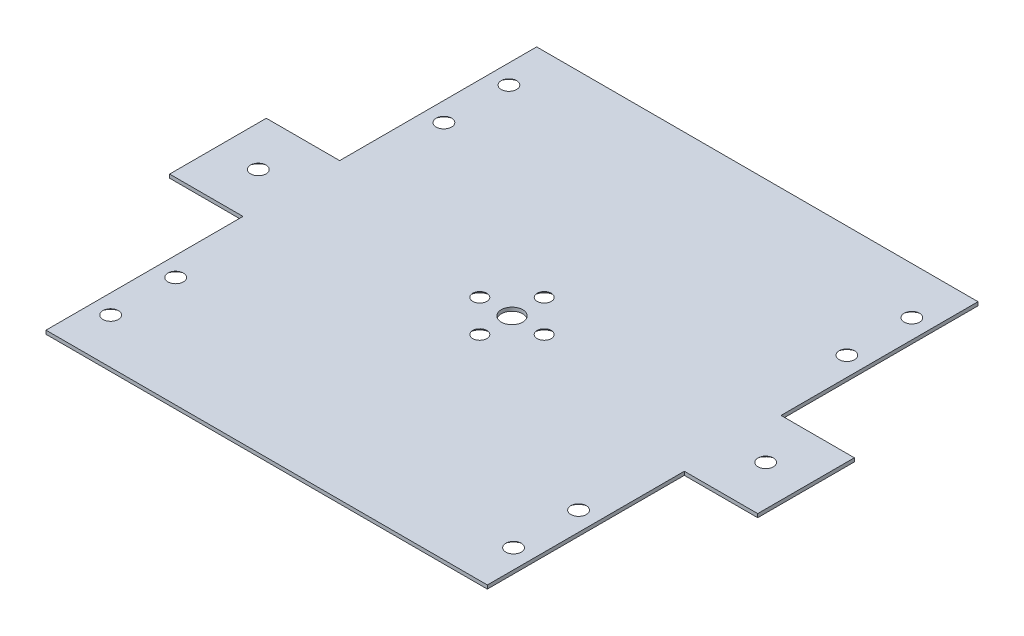
SolidWorks part; units mm, degrees
material "Plain Carbon Steel"
ref_plane "Front Plane" through (0, 0, 0) normal (0, 0, 1) x (1, 0, 0)
ref_plane "Top Plane" through (0, 0, 0) normal (0, 1, 0) x (1, 0, 0)
ref_plane "Right Plane" through (0, 0, 0) normal (1, 0, 0) x (0, 0, -1)
sketch "Sketch1" plane through (0, 0, 0) normal (0, 1, 0) x (1, 0, 0)
  line L1 (-65.0875, 72.3582) -> (65.0875, 72.3582)
  line L2 (-86.7251, 14.2557) -> (-86.7251, -14.2558)
  line L3 (-65.0875, -72.3583) -> (65.0875, -72.3583)
  line L4 (86.7251, 14.2558) -> (86.7251, -14.2558)
  line L9 (-86.7251, -14.2558) -> (-65.0875, -14.2558)
  line L10 (-65.0875, -72.3583) -> (-65.0875, -14.2558)
  line L14 (-86.7251, 14.2557) -> (-65.0875, 14.2558)
  line L15 (-65.0875, 72.3582) -> (-65.0875, 14.2558)
  line L18 (86.7251, -14.2558) -> (65.0875, -14.2558)
  line L19 (65.0875, -72.3583) -> (65.0875, -14.2558)
  line L23 (86.7251, 14.2558) -> (65.0875, 14.2557)
  line L24 (65.0875, 72.3582) -> (65.0875, 14.2557)
  dimension "D1" = 130.175
  dimension "D2" = 28.5115
  dimension "D3" = 21.6376
  dimension "D5" = 65.0875
  dimension "D6" = 14.2558
  dimension "D7" = 144.7165
extrude "Boss-Extrude1" add sketch "Sketch1" along normal blind 1.0668
ref_plane "Plane1" through (0, 0, 0) normal (0, 0, -1) x (-1, 0, 0)
hole_wizard "CSK for #6 Flat Head Machine Screw (100)1" positions "Sketch3" profile "Sketch2" countersink size "#6" standard "ANSI Inch" end condition through all
sketch "Sketch3" plane through (0, 0, 0) normal (0, -1, 0) x (-1, 0, 0)
  line L0 (86.7251, 14.2557) -> (86.7251, -14.2558) construction
  line L1 (-86.7251, -14.2558) -> (-86.7251, 14.2558) construction
  point P0 (59.4201, -58.9598)
  point P3 (59.4201, 58.5152)
  point P6 (-59.4201, 58.5152)
  point P9 (-59.4201, -58.9598)
  point P12 (-59.4201, -39.7828)
  point P17 (59.4201, 39.3382)
  point P20 (-59.4201, 39.3382)
  point P26 (59.4201, -39.7828)
  point P29 (74.8189, 0)
  point P32 (-74.8189, 0)
  point P39 (86.7251, 0)
  point P46 (-86.7251, 0)
sketch "Sketch2" plane through (-59.4201, 0, 58.9598) normal (1, 0, 0) x (0, 0, -1)
  line L0 (0, 0) -> (0, 1.0668)
  line L1 (0, 1.0668) -> (1.8986, 1.0668)
  line L2 (1.8986, 1.0668) -> (1.8986, 1.38)
  line L3 (1.8986, 1.38) -> (3.5433, 0)
  line L5 (3.5433, 0) -> (0, 0)
  line L6 (-1.8986, 1.38) -> (-3.5433, 0) construction
  line L11 (0, -6.35) -> (0, 107.95) construction
  dimension "Thru Hole Dia." = 3.7973
  dimension "Thru Hole Depth" = 1.0668
  dimension "Near C'Sink Dia." = 7.0866
  dimension "Near C'Sink Angle" = 100
sketch "Sketch4" plane through (0, 0, 0) normal (0, -1, 0) x (1, 0, 0)
  line L2 (-86.7251, -14.2557) -> (-86.7251, 14.2558) construction
  line L3 (65.0875, -72.3582) -> (-65.0875, -72.3582) construction
  circle A1 centre (0, 0) radius 3.175
  point P4 (-86.7251, 0)
  point P7 (0, -72.3582)
  dimension "D1" = 6.35
extrude "Cut-Extrude1" cut sketch "Sketch4" against normal through all
hole_wizard "CSK for M3 Flat Head Machine Screw2" positions "Sketch6" profile "Sketch5" countersink size "M3" standard "ANSI Metric" end condition through all
sketch "Sketch6" plane through (0, 0, 0) normal (0, -1, 0) x (-1, 0, 0)
  circle A0 centre (0, 0) radius 8 construction
  circle A1 centre (0, 0) radius 9.5 construction
  point P7 (-9.5, 0)
  point P9 (9.5, 0)
  point P11 (0, 9.5)
  point P13 (0, -9.5)
  dimension "D1" = 16
  dimension "D2" = 19
sketch "Sketch5" plane through (9.5, 0, 0) normal (1, 0, 0) x (0, 0, -1)
  line L0 (0, 0) -> (0, 1.0668)
  line L1 (0, 1.0668) -> (1.7, 1.0668)
  line L2 (1.7, 1.0668) -> (1.7, 1.45)
  line L3 (1.7, 1.45) -> (3.15, 0)
  line L5 (3.15, 0) -> (0, 0)
  line L6 (-1.7, 1.45) -> (-3.15, 0) construction
  line L11 (0, -6.35) -> (0, 107.95) construction
  dimension "Thru Hole Dia." = 3.4
  dimension "Thru Hole Depth" = 1.0668
  dimension "Near C'Sink Dia." = 6.3
  dimension "Near C'Sink Angle" = 90
sketch "Sketch7" plane through (0, 0, 0) normal (1, 0, 0) x (0, 0, -1)
  line L0 (72.3582, 0) -> (72.3582, 1.0668)
  line L1 (72.3582, 1.0668) -> (72.3582, 0) construction
  line L2 (72.3582, 0) -> (71.7423, 1.0668)
  line L3 (72.3582, 1.0668) -> (14.2558, 1.0668) construction
  line L4 (71.7423, 1.0668) -> (72.3582, 1.0668)
  line L5 (72.3582, 0) -> (14.2558, 0) construction
  dimension "D1" = 60
extrude "Cut-Extrude2" [suppressed] cut sketch "Sketch7" against normal through all and the other way through all
mirror "Mirror1" [suppressed] about plane through (0, 0, 0) normal (0, 0, -1)
sketch "Sketch9" plane through (0, 1.0668, 0) normal (0, 1, 0) x (1, 0, 0)
  line L1 (-51.8963, 65.3923) -> (-53.7294, 68.5673)
  line L2 (-53.7294, 68.5673) -> (-57.3956, 68.5673)
  line L3 (-57.3956, 68.5673) -> (-59.2287, 65.3923)
  line L4 (-59.2287, 65.3923) -> (-57.3956, 62.2173)
  line L5 (-57.3956, 62.2173) -> (-53.7294, 62.2173)
  line L6 (-53.7294, 62.2173) -> (-51.8963, 65.3923)
  line L18 (-65.0875, 72.3582) -> (-65.0875, 14.2558) construction
  line L19 (-61.9125, -69.1833) -> (61.9125, -69.1833)
  line L20 (-61.9125, -69.1833) -> (61.9125, -69.1833)
  line L21 (61.9125, 69.1832) -> (-61.9125, 69.1832)
  line L22 (61.9125, 69.1832) -> (-61.9125, 69.1832)
  line L31 (61.9125, -69.1833) -> (61.9125, -11.0808)
  line L32 (61.9125, -11.0808) -> (83.5501, -11.0808)
  line L33 (83.5501, -11.0808) -> (83.5501, 11.0808)
  line L34 (83.5501, 11.0808) -> (61.9125, 11.0807)
  line L35 (61.9125, 11.0807) -> (61.9125, 69.1832)
  line L37 (-61.9125, 69.1832) -> (-61.9125, 11.0808)
  line L38 (-61.9125, 11.0808) -> (-83.5501, 11.0807)
  line L39 (-83.5501, 11.0807) -> (-83.5501, -11.0808)
  line L40 (-83.5501, -11.0808) -> (-61.9125, -11.0808)
  line L41 (-61.9125, -11.0808) -> (-61.9125, -69.1833)
  line L43 (61.9125, -69.1833) -> (61.9125, -11.0808)
  line L44 (61.9125, -11.0808) -> (83.5501, -11.0808)
  line L45 (83.5501, -11.0808) -> (83.5501, 11.0808)
  line L46 (83.5501, 11.0808) -> (61.9125, 11.0807)
  line L47 (61.9125, 11.0807) -> (61.9125, 69.1832)
  line L49 (-61.9125, 69.1832) -> (-61.9125, 11.0808)
  line L50 (-61.9125, 11.0808) -> (-83.5501, 11.0807)
  line L51 (-83.5501, 11.0807) -> (-83.5501, -11.0808)
  line L52 (-83.5501, -11.0808) -> (-61.9125, -11.0808)
  line L53 (-61.9125, -11.0808) -> (-61.9125, -69.1833)
  circle A0 centre (-55.5625, 65.3923) radius 3.175 construction
  dimension "D2" = 6.35
  dimension "D3" = 9.525
  dimension "D1" = 3.175
extrude "Cut-Extrude3" [suppressed] cut sketch "Sketch9" against normal through all contours L5 L6 L1 L2 L3 L4
pattern_linear "LPattern2" [suppressed] count 8 spacing 12.7
sketch "Sketch10" [suppressed] plane through (0, 1.0668, 0) normal (0, 1, 0) x (1, 0, 0)
  line L0 (-50.4974, 65.3923) -> (-43.1651, 65.3923)
  line L1 (-36.8151, 60.6298) -> (-38.6482, 63.8048)
  line L2 (-38.6482, 63.8048) -> (-42.3143, 63.8048)
  line L3 (-42.3143, 63.8048) -> (-44.1474, 60.6298)
  line L4 (-44.1474, 60.6298) -> (-42.3143, 57.4548)
  line L5 (-42.3143, 57.4548) -> (-38.6482, 57.4548)
  line L6 (-38.6482, 57.4548) -> (-36.8151, 60.6298)
  line L7 (-46.8312, 65.3923) -> (-46.8312, 68.5673)
  line L8 (-44.9982, 68.5673) -> (-48.6643, 68.5673) construction
  circle A0 centre (-40.4812, 60.6298) radius 3.175 construction
  dimension "D1" = 6.35
  dimension "D2" = 1.5875
  dimension "D3" = 6.35
extrude "Cut-Extrude4" [suppressed] cut sketch "Sketch10" against normal through all contours L5 L6 L1 L2 L3 L4
pattern_linear "LPattern3" [suppressed] count 7 spacing 12.7
pattern_linear "LPattern6" [suppressed] count 14 spacing 9.525
equation "\"D6@Sketch1\"=\"D2@Sketch1\"/2"
equation "\"D5@Sketch1\"=\"D1@Sketch1\"/2"
